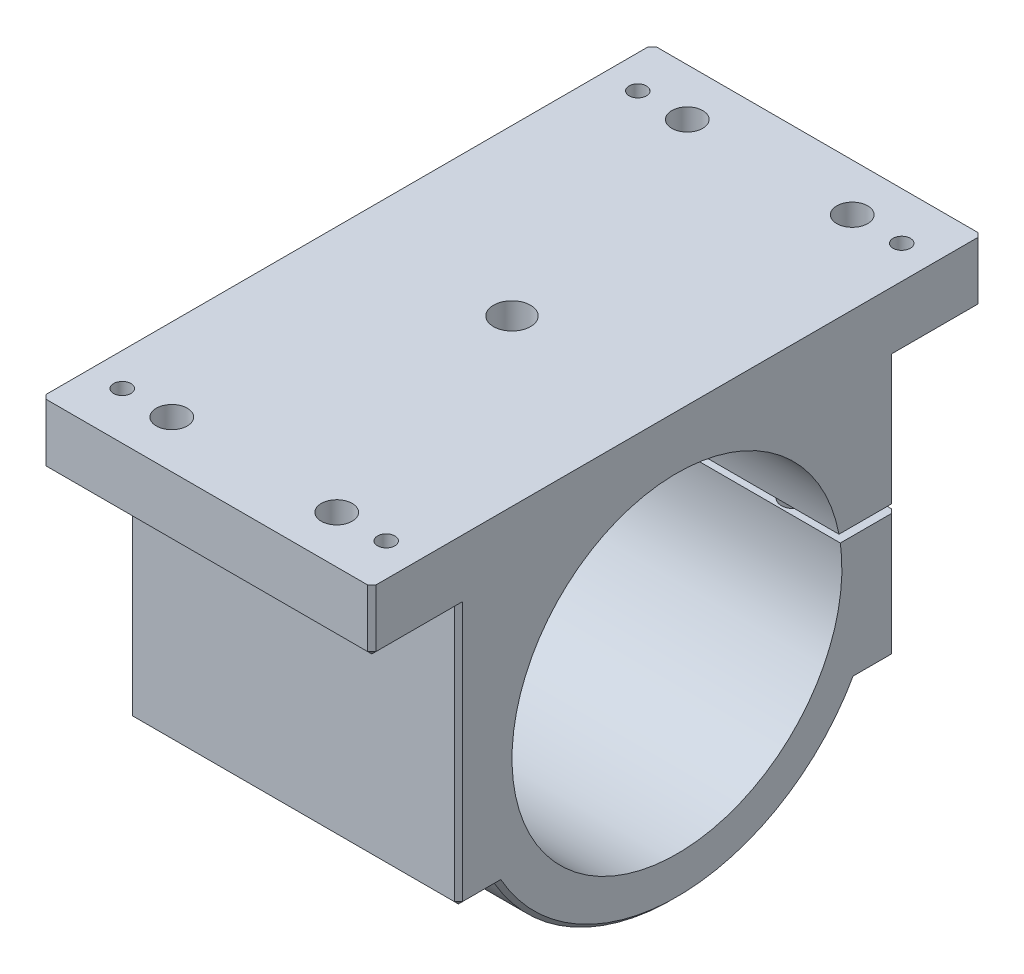
SolidWorks part; units mm, degrees
material "1060 Alloy"
ref_plane "Front Plane" through (0, 0, 0) normal (0, 0, 1) x (1, 0, 0)
ref_plane "Top Plane" through (0, 0, 0) normal (0, 1, 0) x (1, 0, 0)
ref_plane "Right Plane" through (0, 0, 0) normal (1, 0, 0) x (0, 0, -1)
sketch "Sketch1" plane through (0, 0, 0) normal (1, 0, 0) x (0, 0, -1)
  line L0 (0, 122.2832) -> (0, 20.7221) construction
  line L1 (-53, -25) -> (-43.3013, -25)
  line L2 (-53, -25) -> (-53, 38)
  line L3 (-53, 38) -> (-74, 38)
  line L4 (-74, 38) -> (-74, 53)
  line L5 (-74, 53) -> (74, 53)
  line L6 (53, -25) -> (43.3013, -25)
  line L7 (74, 38) -> (74, 53)
  line L8 (53, 38) -> (74, 38)
  line L9 (53, -25) -> (53, 38)
  arc A0 (-43.3013, -25) -> (43.3013, -25) centre (0, 0) ccw
  circle A1 centre (0, 0) radius 40
  point P13 (0, 53)
  dimension "D5" = 80
  dimension "D6" = 50
  dimension "D1" = 148
  dimension "D2" = 15
  dimension "D3" = 21
  dimension "D4" = 63
  dimension "D7" = 53
extrude "Boss-Extrude1" add sketch "Sketch1" along normal mid plane 80
sketch "Sketch2" plane through (0, 0, -53) normal (0, 0, -1) x (-1, 0, 0)
  line L0 (-40, -25) -> (-40, 38) construction
  line L1 (-40, 7.5) -> (40, 7.5)
  line L2 (-40, 7.5) -> (-40, 5.5)
  line L3 (-40, 5.5) -> (40, 5.5)
  line L4 (40, 7.5) -> (40, 5.5)
  line L5 (40, -25) -> (40, 38) construction
  line L6 (-40, 38) -> (40, 38) construction
  dimension "D1" = 2
  dimension "D2" = 30.5
extrude "Cut-Extrude1" cut sketch "Sketch2" against normal blind 19
sketch "Sketch3" plane through (0, -25, 0) normal (0, -1, 0) x (1, 0, 0)
  line L0 (25, -43.3) -> (25, -53) construction
  line L1 (40, -53) -> (-40, -53) construction
  line L2 (25, -43.3) -> (40, -43.3013) construction
  circle A0 centre (25, -43.3) radius 5.5
  dimension "D1" = 11
  dimension "D2" = 9.7
  dimension "D3" = 15
extrude "Cut-Extrude2" cut sketch "Sketch3" along normal through all from offset 3 offset against normal yes
sketch "Sketch4" plane through (0, -22, 0) normal (0, -1, 0) x (1, 0, 0)
  circle A0 centre (25, -43.3) radius 3
  dimension "D1" = 6
extrude "Cut-Extrude3" cut sketch "Sketch4" against normal blind 64.5
pattern_linear "LPattern1" count 3 spacing 25 along (-1, 0, 0) of "Cut-Extrude3", "Cut-Extrude2"
sketch "Sketch5" plane through (0, 53, 0) normal (0, 1, 0) x (1, 0, 0)
  line L0 (-32, 62.5) -> (-20, 62.5) construction
  line L1 (40, 74) -> (-40, 74) construction
  line L2 (-40, 74) -> (-40, -74) construction
  line L3 (-72.0395, 0) -> (41.5363, 0) construction
  line L4 (0, 89.2861) -> (0, -18.3375) construction
  circle A0 centre (0, 0) radius 4.5
  circle A1 centre (-32, 62.5) radius 2.1
  circle A2 centre (-20, 62.5) radius 3.75
  circle A3 centre (32, 62.5) radius 2.1
  circle A4 centre (20, 62.5) radius 3.75
  circle A5 centre (32, -62.5) radius 2.1
  circle A6 centre (20, -62.5) radius 3.75
  circle A7 centre (-20, -62.5) radius 3.75
  circle A8 centre (-32, -62.5) radius 2.1
  dimension "D1" = 7.5
  dimension "D2" = 4.2
  dimension "D6" = 9
  dimension "D3" = 12
  dimension "D4" = 11.5
  dimension "D5" = 8
extrude "Cut-Extrude4" cut sketch "Sketch5" against normal blind 24.5
chamfer "Chamfer1" distance 1 angle 45 24 edges at (40, 22.75, -53) (40, 38, -63.5) (40, 45.5, -74) (0, 38, -74) (-40, 45.5, -74) (-40, 38, -63.5) (-40, 22.75, -53) (40, 6.5, 53) (-40, 6.5, 53) (0, 38, 74) (40, 45.5, 74) (40, 38, 63.5) (-40, 38, 63.5) (-40, 45.5, 74) (40, -9.75, -53) (-40, -9.75, -53) (40, -25, -48.1506) (0, -25, -53) (-40, -25, -48.1506) (40, -50, 0) (40, -25, 48.1506) (0, -25, 53) (-40, -25, 48.1506) (-40, -50, 0)
